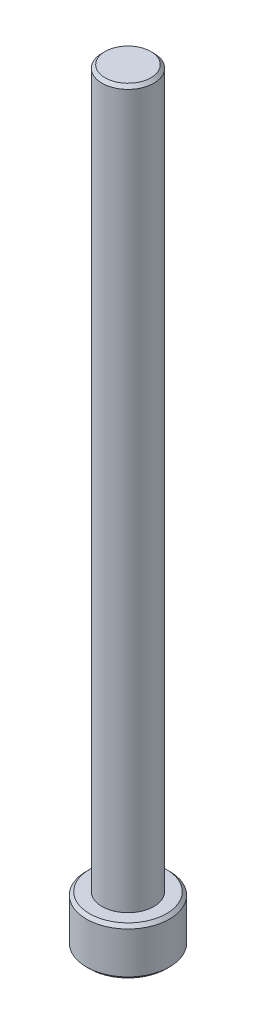
SolidWorks part; units mm, degrees
ref_plane "Front Plane" through (0, 0, 0) normal (0, 0, 1) x (1, 0, 0)
ref_plane "Top Plane" through (0, 0, 0) normal (0, 1, 0) x (1, 0, 0)
ref_plane "Right Plane" through (0, 0, 0) normal (1, 0, 0) x (0, 0, -1)
sketch "Sketch1" plane through (0, 0, 0) normal (0, 1, 0) x (1, 0, 0)
  circle A0 centre (0, 0) radius 4
  dimension "D1" = 8
extrude "Boss-Extrude1" add sketch "Sketch1" along normal blind 4.6
sketch "Sketch2" plane through (0, 4.6, 0) normal (0, 1, 0) x (1, 0, 0)
  circle A0 centre (0, 0) radius 2.5
  dimension "D1" = 5
extrude "Boss-Extrude2" add sketch "Sketch2" along normal blind 69
chamfer "Chamfer1" distance 0.3 angle 45 2 edges at (0, 0, 4) (0, 4.6, 4)
chamfer "Chamfer2" distance 0.3 angle 45 1 edges at (0, 73.6, 2.5)
